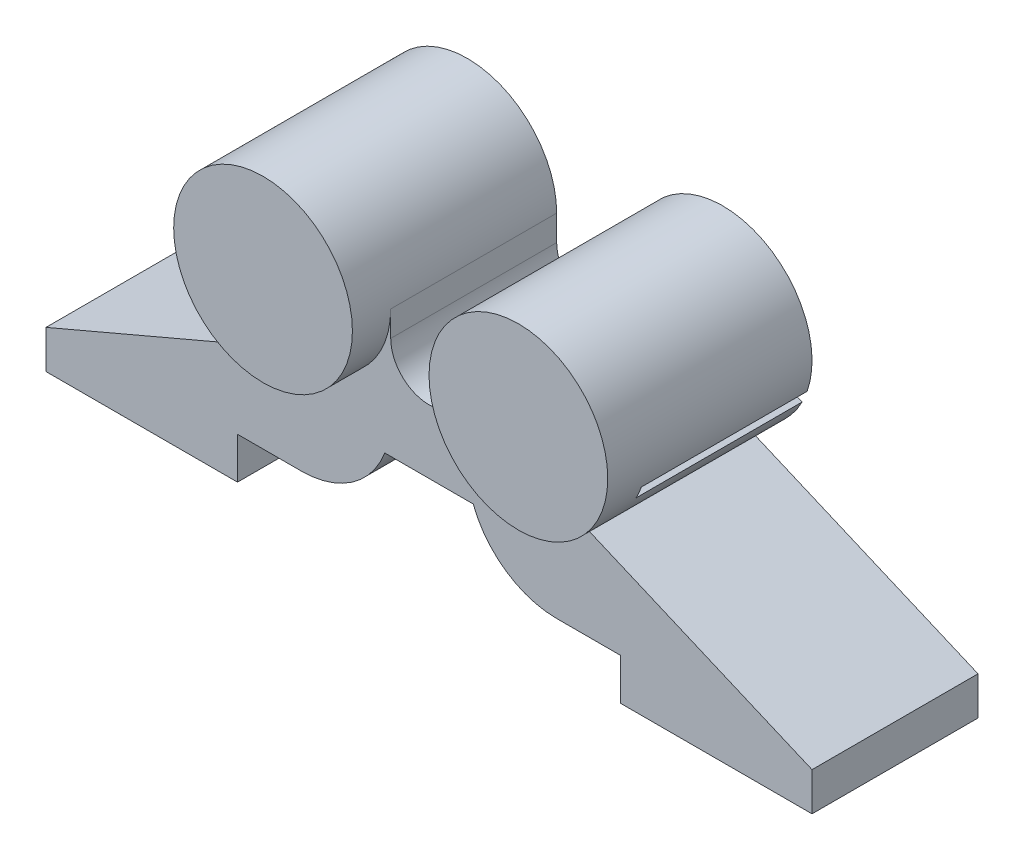
SolidWorks part; units mm, degrees
ref_plane "Front Plane" through (0, 0, 0) normal (0, 0, 1) x (1, 0, 0)
ref_plane "Top Plane" through (0, 0, 0) normal (0, 1, 0) x (1, 0, 0)
ref_plane "Right Plane" through (0, 0, 0) normal (1, 0, 0) x (0, 0, -1)
sketch "Sketch1" plane through (0, 0, 0) normal (0, 0, 1) x (1, 0, 0)
  line L0 (0, -47.8538) -> (0, 47.8538) construction
  line L1 (10, -14.5) -> (15, -14.5)
  line L2 (15, -14.5) -> (15, -17.75)
  line L3 (15, -17.75) -> (30, -17.75)
  line L4 (30, -17.75) -> (30, -14.75)
  line L5 (30, -14.75) -> (13, -7.5) construction
  line L6 (0, -5) -> (3.4617, -5) construction
  line L7 (3.4617, -5) -> (3.4617, -10) construction
  line L8 (3.4617, -10) -> (0, -10)
  line L9 (30, -14.75) -> (16.8089, -9.1244)
  line L10 (0, -10) -> (0, -5)
  line L11 (16.8089, -9.1244) -> (11.4644, -6.8451)
  line L12 (3, 0) -> (3, -2)
  circle A0 centre (10, -7.5) radius 7 construction
  circle A1 centre (10, 0) radius 7
  arc A2 (3.4617, -10) -> (10, -14.5) centre (10, -7.5) ccw
  arc A3 (0, -5) -> (3, -2) centre (0, -2) ccw
  point P5 (0, 0)
  point P15 (3.4617, -7.5)
  dimension "D1" = 14
  dimension "D2" = 20
  dimension "D3" = 15
  dimension "D4" = 3
  dimension "D5" = 3.25
  dimension "D6" = 7.5
  dimension "D7" = 30
  dimension "D8" = 3
  dimension "D9" = 5
extrude "Boss-Extrude1" add sketch "Sketch1" along normal blind 13 contours A1 | A3 L10 L8 A2 L1 L2 L3 L4 L9 L11 A1 L12
sketch "Sketch2" plane through (0, 0, 13) normal (0, 0, 1) x (1, 0, 0)
  circle A0 centre (10, 0) radius 7 construction
  circle A1 centre (10, 0) radius 7
extrude "Boss-Extrude2" add sketch "Sketch2" along normal blind 3
sketch "Sketch3" plane through (0, 0, 0) normal (0, 0, 1) x (1, 0, 0)
  line L0 (12.5248, -1.6203) -> (16.6641, -3.3856)
  line L1 (16.6641, -3.3856) -> (17.0564, -2.4658)
  line L2 (17.0564, -2.4658) -> (12.9171, -0.7005)
  line L3 (16.8089, -9.1244) -> (11.4644, -6.8451) construction
  circle A0 centre (10, 0) radius 3
  dimension "D1" = 6
  dimension "D2" = 1
  dimension "D3" = 4.5
extrude "Cut-Extrude1" cut sketch "Sketch3" along normal blind 13 contours A0 | A0 L0 L1 L2
mirror "Mirror1" about plane through (0, 0, 0) normal (1, 0, 0) of bodies 112
